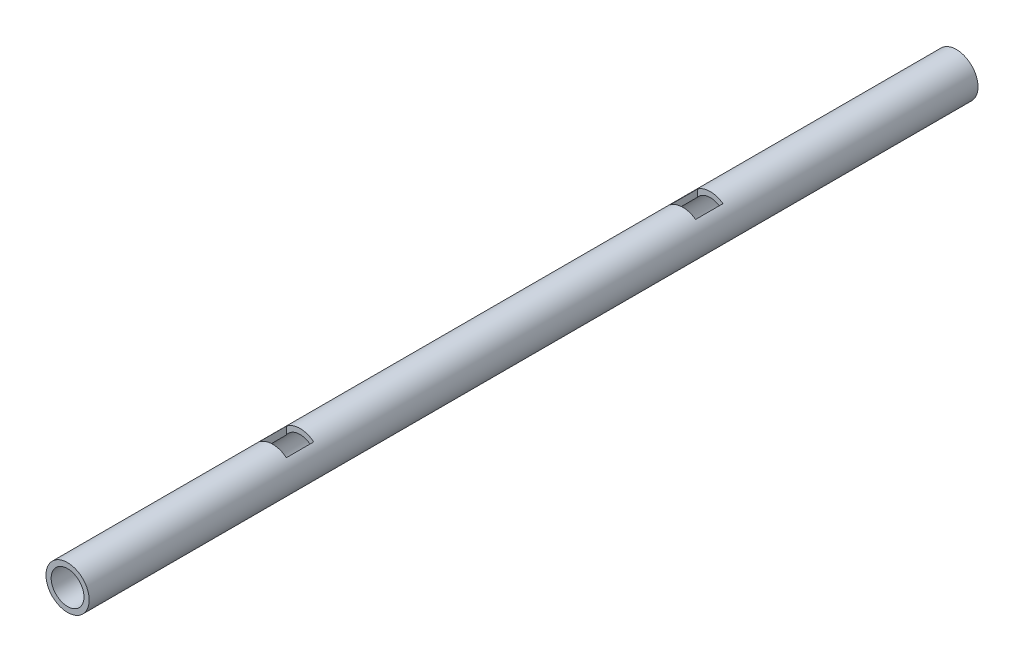
SolidWorks part; units mm, degrees
ref_plane "Alzado" through (0, 0, 0) normal (0, 0, 1) x (1, 0, 0)
ref_plane "Planta" through (0, 0, 0) normal (0, 1, 0) x (1, 0, 0)
ref_plane "Vista lateral" through (0, 0, 0) normal (1, 0, 0) x (0, 0, -1)
sketch "Croquis1" plane through (0, 0, 0) normal (0, 0, 1) x (1, 0, 0)
  circle A0 centre (0, 0) radius 7.9
  dimension "D1" = 15.8
extrude "Saliente-Extruir1" add sketch "Croquis1" along normal mid plane 325
sketch "Croquis3" plane through (0, 0, 162.5) normal (0, 0, 1) x (1, 0, 0)
  circle A0 centre (0, 0) radius 6
extrude "Cortar-Extruir1" cut sketch "Croquis3" against normal through all
sketch "Croquis4" plane through (0, 0, 0) normal (0, 1, 0) x (1, 0, 0)
  line L0 (-7.9, -162.5) -> (7.9, -162.5) construction
  line L1 (-5, -87.5) -> (5, -87.5)
  line L2 (-5, -87.5) -> (-5, -77.5)
  line L3 (-5, -77.5) -> (5, -77.5)
  line L4 (5, -87.5) -> (5, -77.5)
  line L5 (-5, -87.5) -> (5, -77.5) construction
  line L6 (-5, -77.5) -> (5, -87.5) construction
  point P0 (0, -82.5)
  dimension "D1" = 75
extrude "Cortar-Extruir2" cut sketch "Croquis4" along normal up to surface (6.1164 mm away)
sketch "Croquis5" plane through (0, 0, 0) normal (0, 1, 0) x (1, 0, 0)
  line L0 (0, -162.5) -> (0, 62.5) construction
  line L1 (-7.9, -162.5) -> (7.9, -162.5) construction
  line L3 (-4.6452, 72.5) -> (4.6452, 72.5)
  line L4 (-4.6452, 72.5) -> (-4.6452, 62.5)
  line L5 (-4.6452, 62.5) -> (4.6452, 62.5)
  line L6 (4.6452, 72.5) -> (4.6452, 62.5)
  point P5 (0, 88.3514)
  point P10 (0, 62.5)
  dimension "D1" = 10
  dimension "D2" = 225
extrude "Cortar-Extruir3" cut sketch "Croquis5" along normal up to surface (6.39 mm away)
